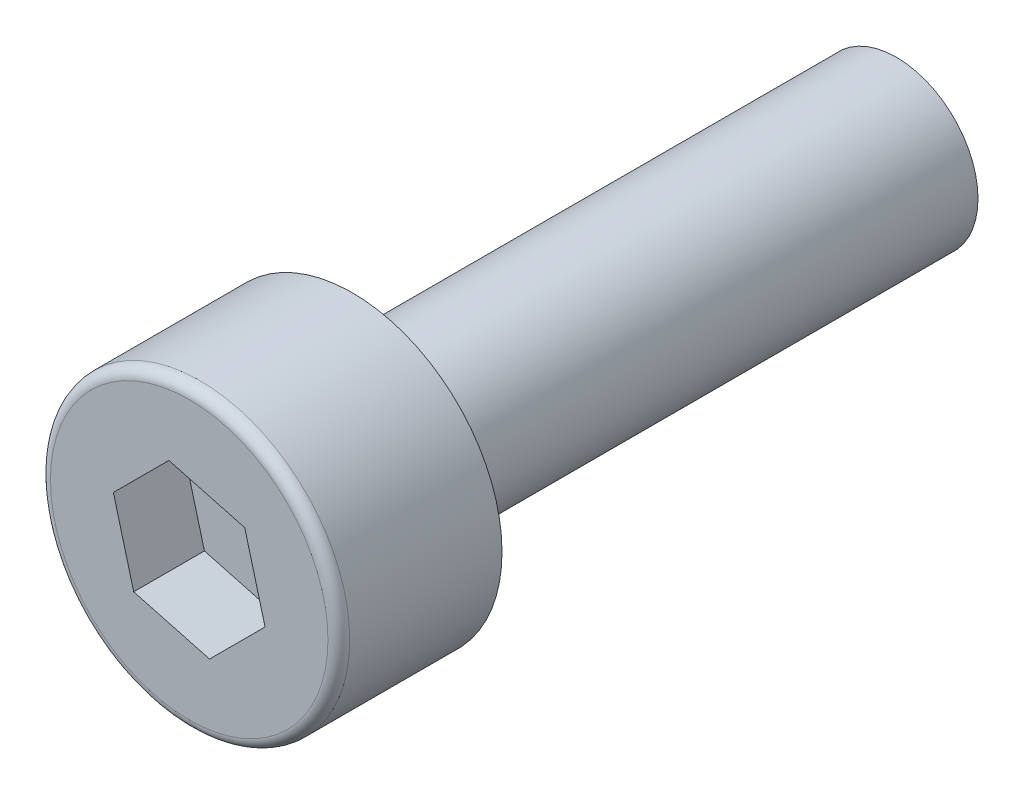
SolidWorks part; units mm, degrees
ref_plane "前视基准面" through (0, 0, 0) normal (0, 0, 1) x (1, 0, 0)
ref_plane "上视基准面" through (0, 0, 0) normal (0, 1, 0) x (1, 0, 0)
ref_plane "右视基准面" through (0, 0, 0) normal (1, 0, 0) x (0, 0, -1)
sketch "草图1" plane through (0, 0, 0) normal (0, 0, 1) x (1, 0, 0)
  circle A0 centre (0, 0) radius 2.75
  dimension "D1" = 5.5
extrude "凸台-拉伸1" add sketch "草图1" along normal blind 3
sketch "草图2" plane through (0, 0, 3) normal (0, 0, 1) x (1, 0, 0)
  line L1 (-1.0206, -1.0206) -> (0.3736, -1.3942)
  line L2 (0.3736, -1.3942) -> (1.3942, -0.3736)
  line L3 (1.3942, -0.3736) -> (1.0206, 1.0206)
  line L4 (1.0206, 1.0206) -> (-0.3736, 1.3942)
  line L5 (-0.3736, 1.3942) -> (-1.3942, 0.3736)
  line L6 (-1.3942, 0.3736) -> (-1.0206, -1.0206)
  circle A0 centre (0, 0) radius 1.25 construction
  dimension "D1" = 2.5
extrude "切除-拉伸1" cut sketch "草图2" against normal blind 1.3
sketch "草图3" plane through (0, 0, 0) normal (0, 0, -1) x (-1, 0, 0)
  circle A0 centre (0, 0) radius 1.5
  dimension "D1" = 3
extrude "凸台-拉伸2" add sketch "草图3" along normal blind 10
fillet "圆角1" radius 0.2 1 edges at (2.75, 0, 3)
